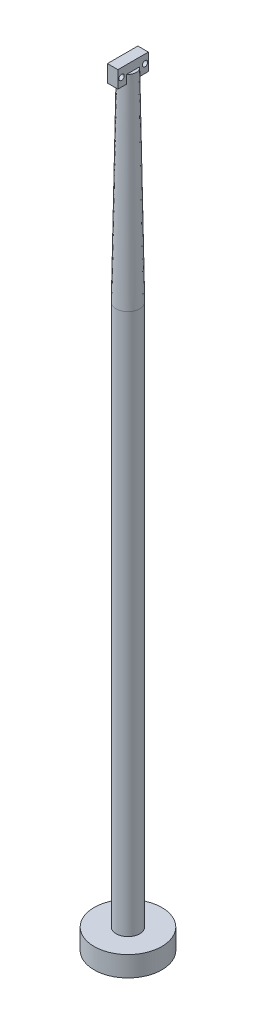
SolidWorks part; units mm, degrees
ref_plane "Alzado" through (0, 0, 0) normal (0, 0, 1) x (1, 0, 0)
ref_plane "Planta" through (0, 0, 0) normal (0, 1, 0) x (1, 0, 0)
ref_plane "Vista lateral" through (0, 0, 0) normal (1, 0, 0) x (0, 0, -1)
sketch "Croquis1" plane through (0, 0, 0) normal (0, 1, 0) x (1, 0, 0)
  circle A0 centre (0, 0) radius 500
  dimension "D1" = 1000
extrude "Saliente-Extruir1" add sketch "Croquis1" along normal blind 300
sketch "Croquis2" plane through (0, 300, 0) normal (0, 1, 0) x (1, 0, 0)
  circle A0 centre (0, 0) radius 175
  dimension "D1" = 350
extrude "Saliente-Extruir3" add sketch "Croquis2" along normal blind 8000 contours A0
sketch "Croquis4" plane through (0, 8300, 0) normal (0, 1, 0) x (1, 0, 0)
  circle A0 centre (0, 0) radius 175
extrude "Saliente-Extruir5" add sketch "Croquis4" along normal blind 3000 draft 1
ref_plane "Plano1" through (0, 0, 0) normal (0, 0, 1) x (1, 0, 0)
sketch "Croquis5" plane through (0, 11300, 0) normal (0, 1, 0) x (1, 0, 0)
  line L0 (0, 0) -> (0, -122.6348)
  circle A0 centre (0, 0) radius 122.6348 construction
ref_plane "Plano2" through (0, 0, 0) normal (-1, 0, 0) x (0, 0, 1)
sketch "Croquis6" plane through (0, 0, 0) normal (-1, 0, 0) x (0, 0, 1)
  line L0 (122.6348, 11300) -> (-122.6348, 11300) construction
  line L1 (225, 11425) -> (-225, 11425)
  line L2 (225, 11425) -> (225, 11175)
  line L3 (225, 11175) -> (-225, 11175)
  line L4 (-225, 11425) -> (-225, 11175)
  line L5 (225, 11425) -> (-225, 11175) construction
  line L6 (225, 11175) -> (-225, 11425) construction
  circle A0 centre (-176.0053, 11300) radius 40
  circle A1 centre (171.3729, 11300) radius 40
  point P0 (0, 11300)
  point P11 (-176.0053, 11300)
  point P12 (171.3729, 11300)
  dimension "D1" = 80
  dimension "D2" = 80
  dimension "D3" = 250
  dimension "D4" = 450
extrude "Saliente-Extruir6" add sketch "Croquis6" along normal blind 79 and the other way blind 76
